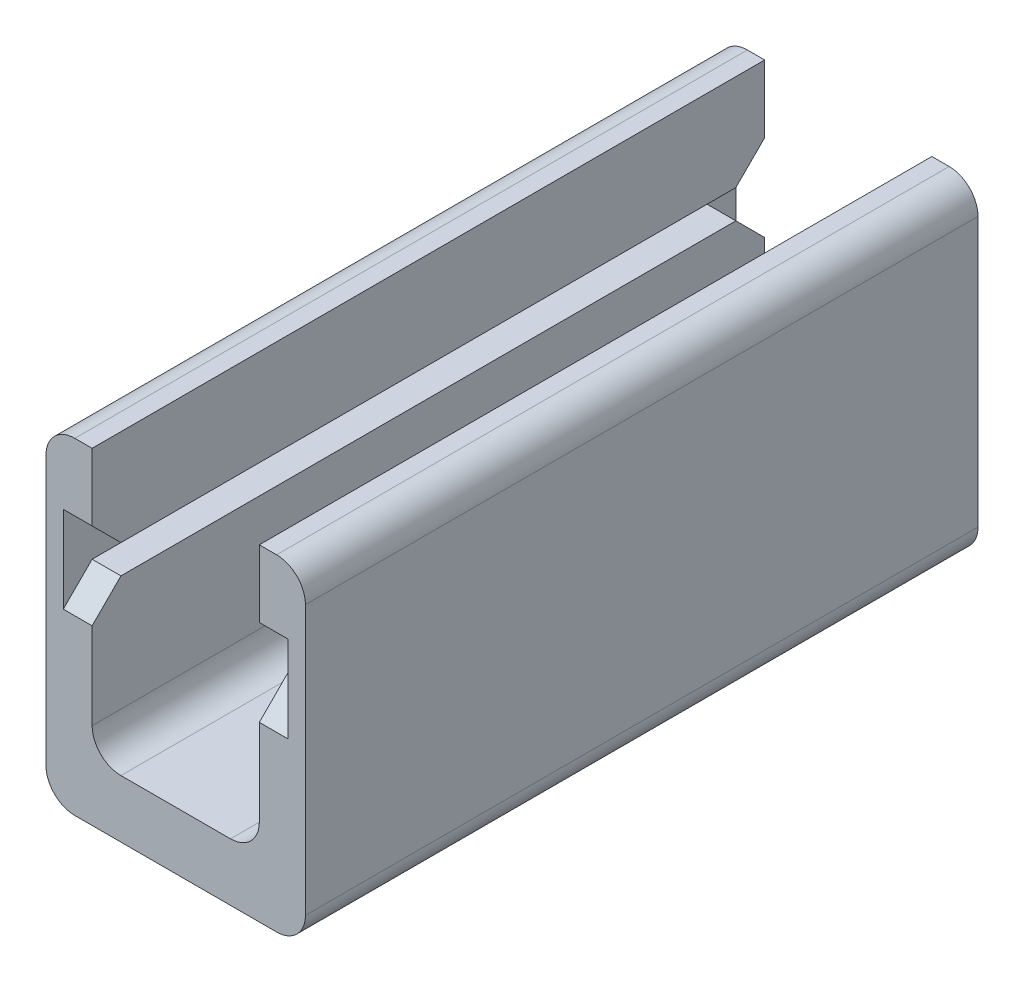
SolidWorks part; units mm, degrees
ref_plane "Ebene vorne" through (0, 0, 0) normal (0, 0, 1) x (1, 0, 0)
ref_plane "Ebene oben" through (0, 0, 0) normal (0, 1, 0) x (1, 0, 0)
ref_plane "Ebene rechts" through (0, 0, 0) normal (1, 0, 0) x (0, 0, -1)
sketch "Skizze1" plane through (0, 0, 0) normal (0, 0, 1) x (1, 0, 0)
  line L0 (-6.75, 0) -> (6.75, 0)
  line L1 (6.75, 0) -> (6.75, 17)
  line L2 (6.75, 17) -> (4.35, 17)
  line L3 (4.35, 17) -> (4.35, 12)
  line L4 (4.35, 12) -> (5.85, 12)
  line L5 (5.85, 12) -> (5.85, 10.5)
  line L6 (5.85, 10.5) -> (4.35, 10.5)
  line L7 (4.35, 10.5) -> (4.35, 3)
  line L8 (4.35, 3) -> (-4.35, 3)
  line L9 (-4.35, 3) -> (-4.35, 10.5)
  line L10 (-4.35, 10.5) -> (-5.85, 10.5)
  line L11 (-5.85, 10.5) -> (-5.85, 12)
  line L12 (-5.85, 12) -> (-4.35, 12)
  line L13 (-4.35, 12) -> (-4.35, 17)
  line L14 (-4.35, 17) -> (-6.75, 17)
  line L15 (-6.75, 17) -> (-6.75, 0)
  line L16 (0, 0) -> (0, 14.1609) construction
  point P0 (0, 0)
  dimension "D1" = 13.5
  dimension "D2" = 1.5
  dimension "D3" = 1.5
  dimension "D4" = 5
  dimension "D5" = 17
  dimension "D6" = 3
  dimension "D7" = 11.7
extrude "Aufsatz-Linear austragen1" add sketch "Skizze1" along normal blind 35
fillet "Verrundung1" radius 1.5 6 edges at (-6.75, 17, 17.5) (6.75, 17, 17.5) (6.75, 0, 17.5) (-6.75, 0, 17.5) (4.35, 3, 17.5) (-4.35, 3, 17.5)
chamfer "Fase1" distance 1.5 angle 45 8 edges at (5.1, 10.5, 0) (5.1, 12, 0) (-5.1, 12, 0) (-5.1, 10.5, 0) (5.1, 10.5, 35) (5.1, 12, 35) (-5.1, 10.5, 35) (-5.1, 12, 35)
